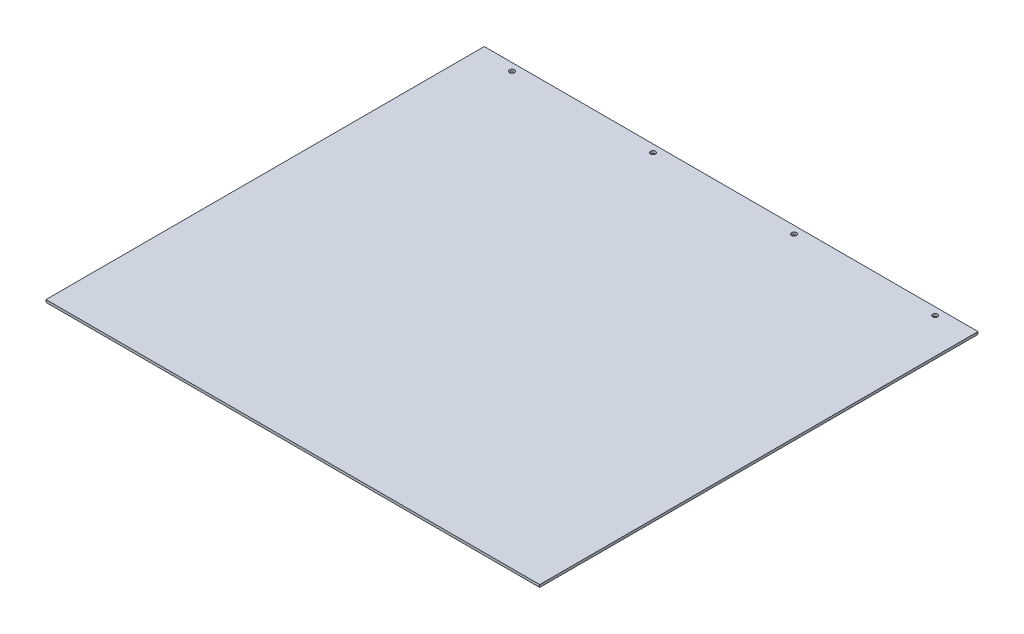
SolidWorks part; units mm, degrees
material "Pine"
ref_plane "Front Plane" through (0, 0, 0) normal (0, 0, 1) x (1, 0, 0)
ref_plane "Top Plane" through (0, 0, 0) normal (0, 1, 0) x (1, 0, 0)
ref_plane "Right Plane" through (0, 0, 0) normal (1, 0, 0) x (0, 0, -1)
sketch "Sketch1" plane through (0, 0, 0) normal (0, 1, 0) x (1, 0, 0)
  line L1 (0, 0) -> (622.3, 0)
  line L2 (0, 0) -> (0, 552.45)
  line L3 (0, 552.45) -> (622.3, 552.45)
  line L4 (622.3, 0) -> (622.3, 552.45)
  circle A4 centre (44.45, 542.925) radius 3.175
  circle A5 centre (222.25, 542.925) radius 3.175
  circle A6 centre (577.85, 542.925) radius 3.175
  circle A7 centre (400.05, 542.925) radius 3.175
  point P0 (0, 0)
  point P1 (0, 0)
  point P2 (0, 0)
  point P3 (0, 0)
  point P7 (0, 0)
  point P10 (622.3, 0)
  point P14 (0, 0)
  point P15 (0, 552.45)
  dimension "D4" = 6.35
  dimension "D7" = 6.35
  dimension "D8" = 6.35
  dimension "D9" = 6.35
  dimension "D11" = 9.525
  dimension "D12" = 9.525
  dimension "D15" = 44.45
  dimension "D1" = 552.45
  dimension "D2" = 622.3
  dimension "D5" = 9.525
  dimension "D6" = 44.45
  dimension "D10" = 9.525
  dimension "D13" = 222.25
  dimension "D14" = 222.25
extrude "Boss-Extrude1" add sketch "Sketch1" along normal blind 3.175
